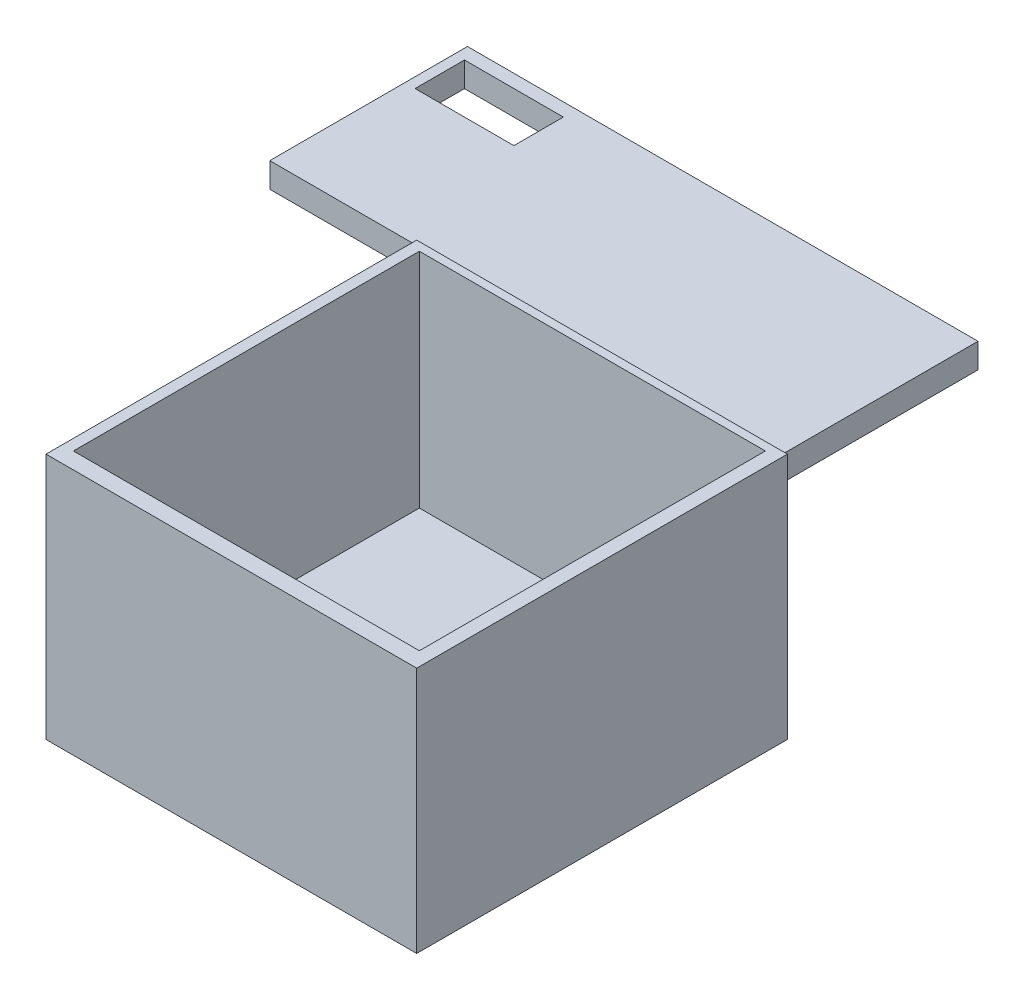
SolidWorks part; units mm, degrees
ref_plane "前视基准面" through (0, 0, 0) normal (0, 0, 1) x (1, 0, 0)
ref_plane "上视基准面" through (0, 0, 0) normal (0, 1, 0) x (1, 0, 0)
ref_plane "右视基准面" through (0, 0, 0) normal (1, 0, 0) x (0, 0, -1)
other "Configuration Table"
sketch "草图1" plane through (0, 0, 0) normal (0, 1, 0) x (1, 0, 0)
  line L1 (-136.9896, 6.0554) -> (13.0104, 6.0554)
  line L2 (-136.9896, 6.0554) -> (-136.9896, -143.9446)
  line L3 (-136.9896, -143.9446) -> (13.0104, -143.9446)
  line L4 (13.0104, 6.0554) -> (13.0104, -143.9446)
  dimension "D1" = 150
  dimension "D2" = 150
extrude "凸台-拉伸1" add sketch "草图1" along normal blind 100
sketch "草图2" plane through (0, 100, 0) normal (0, 1, 0) x (1, 0, 0)
  line L1 (-132.5474, 2.7044) -> (7.4526, 2.7044)
  line L2 (-132.5474, 2.7044) -> (-132.5474, -137.2956)
  line L3 (-132.5474, -137.2956) -> (7.4526, -137.2956)
  line L4 (7.4526, 2.7044) -> (7.4526, -137.2956)
  dimension "D1" = 140
  dimension "D2" = 140
extrude "切除-拉伸1" cut sketch "草图2" against normal blind 90
sketch "草图3" plane through (0, 0, -6.0554) normal (0, 0, -1) x (-1, 0, 0)
  line L1 (-10.1416, 98.1247) -> (196.4429, 98.1247)
  line L2 (-10.1416, 98.1247) -> (-10.1416, 88.08)
  line L3 (-10.1416, 88.08) -> (196.4429, 88.08)
  line L4 (196.4429, 98.1247) -> (196.4429, 88.08)
  point P4 (196.4429, 98.1247)
extrude "凸台-拉伸2" add sketch "草图3" along normal blind 80
sketch "草图4" plane through (0, 88.08, 0) normal (0, -1, 0) x (1, 0, 0)
  line L1 (-192.313, -60.7128) -> (-152.313, -60.7128)
  line L2 (-192.313, -60.7128) -> (-192.313, -80.7128)
  line L3 (-192.313, -80.7128) -> (-152.313, -80.7128)
  line L4 (-152.313, -60.7128) -> (-152.313, -80.7128)
  dimension "D1" = 20
  dimension "D2" = 40
extrude "切除-拉伸2" cut sketch "草图4" against normal blind 20
